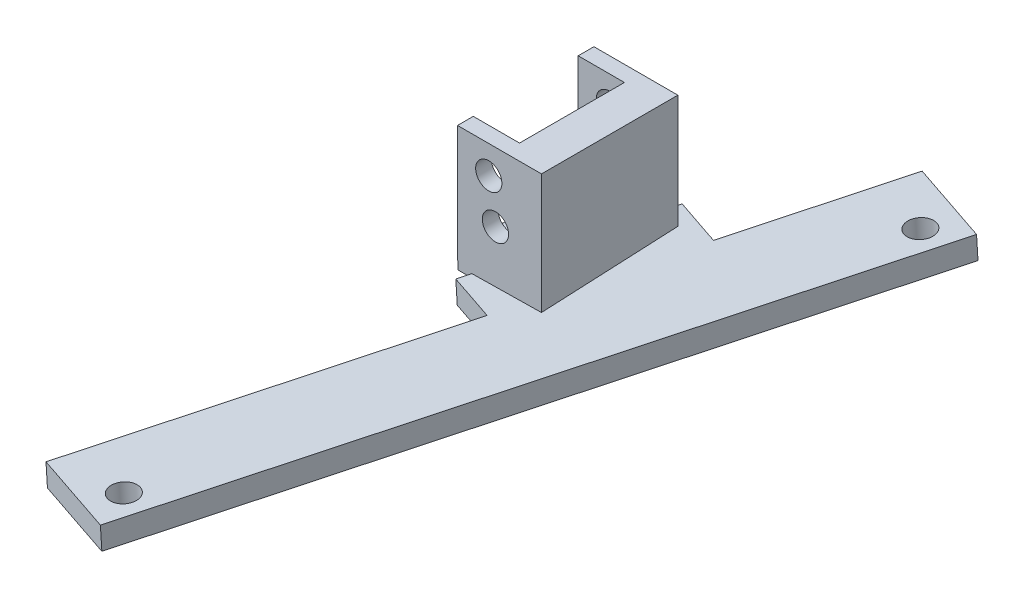
SolidWorks part; units mm, degrees
ref_plane "Front Plane" through (0, 0, 0) normal (0, 0, 1) x (1, 0, 0)
ref_plane "Top Plane" through (0, 0, 0) normal (0, 1, 0) x (1, 0, 0)
ref_plane "Right Plane" through (0, 0, 0) normal (1, 0, 0) x (0, 0, -1)
sketch "Sketch1" plane through (0, 0, 0) normal (0, 0, 1) x (1, 0, 0)
  line L0 (427.4923, 249.3739) -> (458.8626, 254.5214) construction
  line L1 (448.4353, 278.7761) -> (468.7553, 278.7761)
  line L2 (448.4353, 278.7761) -> (448.4353, 250.4861)
  line L3 (448.4353, 250.4861) -> (468.7553, 250.4861)
  line L4 (468.7553, 278.7761) -> (468.7553, 250.4861)
  line L5 (427.4923, 249.3739) -> (458.8626, 254.5214)
  line L6 (448.4353, 252.8104) -> (458.8626, 254.5214)
  arc A0 (461.3669, 277.5061) -> (454.7498, 279.5862) centre (455.9966, 271.9877) ccw construction
  arc A1 (463.4772, 270.1621) -> (461.3669, 277.5061) centre (455.9966, 271.9877) ccw construction
  arc A2 (463.4772, 270.1621) -> (464.1208, 266.2396) centre (468.4124, 268.9577) ccw construction
  arc A3 (464.4679, 258.6072) -> (464.1208, 266.2396) centre (457.6159, 262.1197) ccw construction
  arc A4 (458.8626, 254.5214) -> (464.4679, 258.6072) centre (457.6159, 262.1197) ccw construction
  arc A5 (461.3669, 277.5061) -> (454.7498, 279.5862) centre (455.9966, 271.9877) ccw
  arc A6 (463.4772, 270.1621) -> (461.3669, 277.5061) centre (455.9966, 271.9877) ccw
  arc A7 (463.4772, 270.1621) -> (464.1208, 266.2396) centre (468.4124, 268.9577) ccw
  arc A8 (464.4679, 258.6072) -> (464.1208, 266.2396) centre (457.6159, 262.1197) ccw
  arc A9 (458.8626, 254.5214) -> (464.4679, 258.6072) centre (457.6159, 262.1197) ccw
  arc A10 (458.8626, 254.5214) -> (464.4679, 258.6072) centre (457.6159, 262.1197) ccw
  arc A11 (464.4679, 258.6072) -> (464.1208, 266.2396) centre (457.6159, 262.1197) ccw
  arc A12 (464.1208, 266.2396) -> (463.4772, 270.1621) centre (468.4124, 268.9577) cw
  arc A13 (463.4772, 270.1621) -> (461.3669, 277.5061) centre (455.9966, 271.9877) ccw
  arc A14 (461.3669, 277.5061) -> (459.6312, 278.7761) centre (455.9966, 271.9877) ccw
  circle A15 centre (457.6159, 262.1197) radius 3.175
  circle A16 centre (455.9966, 271.9877) radius 3.175
  dimension "D1" = 4.0353
  dimension "D2" = 1.27
  dimension "D3" = 20.32
  dimension "D4" = 10.16
extrude "Boss-Extrude1" add sketch "Sketch1" against normal blind 29.21 contours A9 L5 L2 L3 L4 L1 A5 A6 A7 A8
sketch "Sketch2" plane through (0, 0, 0) normal (0, 0, 1) x (1, 0, 0)
  line L0 (448.4353, 252.8104) -> (448.4353, 278.7761)
  line L1 (448.4353, 278.7761) -> (468.7553, 278.7761)
  line L2 (468.7553, 278.7761) -> (468.7553, 250.4861)
  line L3 (468.7553, 250.4861) -> (448.4353, 250.4861)
  line L4 (448.4353, 250.4861) -> (448.4353, 252.8104)
  circle A0 centre (455.9966, 271.9877) radius 3.175
  circle A1 centre (457.6159, 262.1197) radius 3.175
  dimension "D1" = 6.35
  dimension "D2" = 6.35
extrude "Boss-Extrude2" add sketch "Sketch2" along normal blind 3.81
sketch "Sketch3" plane through (0, 0, -25.4) normal (0, 0, -1) x (-1, 0, 0)
  line L0 (-448.4353, 252.8104) -> (-458.8626, 254.5214) construction
  line L1 (-448.4353, 252.8104) -> (-458.8626, 254.5214)
  line L2 (-448.4353, 252.8104) -> (-448.4353, 278.7761)
  line L3 (-448.4353, 278.7761) -> (-459.6312, 278.7761)
  line L4 (-458.8626, 254.5214) -> (-448.4353, 252.8104)
  arc A0 (-464.1208, 266.2396) -> (-458.8626, 254.5214) centre (-457.6159, 262.1197) ccw construction
  arc A1 (-464.1208, 266.2396) -> (-463.4772, 270.1621) centre (-468.4124, 268.9577) ccw construction
  arc A2 (-459.6312, 278.7761) -> (-463.4772, 270.1621) centre (-455.9966, 271.9877) ccw construction
  arc A3 (-464.1208, 266.2396) -> (-458.8626, 254.5214) centre (-457.6159, 262.1197) ccw
  arc A4 (-464.1208, 266.2396) -> (-463.4772, 270.1621) centre (-468.4124, 268.9577) ccw
  arc A5 (-459.6312, 278.7761) -> (-463.4772, 270.1621) centre (-455.9966, 271.9877) ccw
  arc A6 (-459.6312, 278.7761) -> (-463.4772, 270.1621) centre (-455.9966, 271.9877) ccw
  arc A7 (-463.4772, 270.1621) -> (-464.1208, 266.2396) centre (-468.4124, 268.9577) cw
  arc A8 (-464.1208, 266.2396) -> (-458.8626, 254.5214) centre (-457.6159, 262.1197) ccw
  circle A9 centre (-457.6159, 262.1197) radius 3.175
  circle A10 centre (-455.9966, 271.9877) radius 3.175
  line M4 (-423.8853, 271.3557) -> (-461.3669, 277.5061)
  arc M5 (-461.3669, 277.5061) -> (-463.4772, 270.1621) centre (-455.9966, 271.9877) ccw
  arc M6 (-463.4772, 270.1621) -> (-464.1208, 266.2396) centre (-468.4124, 268.9577) cw
  arc M7 (-464.1208, 266.2396) -> (-464.4679, 258.6072) centre (-457.6159, 262.1197) ccw
  line M8 (-464.4679, 258.6072) -> (-424.8406, 252.1047)
  circle M9 centre (-457.6159, 262.1197) radius 3.175
  circle M10 centre (-455.9966, 271.9877) radius 3.175
  dimension "D1" = 6.35
  dimension "D2" = 6.35
extrude "Boss-Extrude3" add sketch "Sketch3" along normal up to surface (3.81 mm away) contours L2 M8 M4 M5 M6 M7 M9 M10 | A3 L1 L2 M8 | L3 A5 L2 M4 up to face at (460.587, 262.6797, -29.21)
ref_plane "Plane1" through (-3.842, 241.8411, 11.4068) normal (-0.0159, 0.9988, 0.0471) x (0.9999, 0.0158, 0.0007)
sketch "Sketch4" plane through (-3.842, 241.8411, 11.4068) normal (-0.0159, 0.9988, 0.0471) x (0.9999, 0.0158, 0.0007)
  line L0 (459.2158, -85.5005) -> (512.6671, 73.3898)
  line L1 (512.6671, 73.3898) -> (492.8082, 80.0704)
  line L2 (492.8082, 80.0704) -> (480.0779, 42.228)
  line L3 (480.0779, 42.228) -> (468.6402, 46.0757)
  line L4 (468.6402, 46.0757) -> (454.8306, 5.0251)
  line L5 (454.8306, 5.0251) -> (466.2683, 1.1774)
  line L6 (466.2683, 1.1774) -> (439.3569, -78.8198)
  line L7 (439.3569, -78.8198) -> (459.2158, -85.5005)
  circle A0 centre (455.6747, -76.2696) radius 3.175
  circle A1 centre (504.2669, 68.1761) radius 3.175
  dimension "D6" = 39.9263
  dimension "D8" = 6.35
  dimension "D10" = 6.35
  dimension "D2" = 7.62
  dimension "D3" = 7.62
  dimension "D4" = 167.64
  dimension "D5" = 20.9525
  dimension "D7" = 84.4025
  dimension "D9" = 17.0596
  dimension "D11" = 20.9525
  dimension "D12" = 33.02
extrude "Boss-Extrude4" add sketch "Sketch4" against normal blind 5.588
sketch "Sketch5" plane through (0, 0, 3.81) normal (0, 0, 1) x (1, 0, 0)
  line L0 (468.7553, 250.4861) -> (448.5605, 250.4861)
  line L1 (448.4353, 250.4861) -> (468.7553, 250.4861) construction
  line L2 (448.5605, 250.4861) -> (448.5605, 248.529)
  line L3 (448.5605, 248.529) -> (468.7553, 248.3932)
  line L4 (468.7553, 248.3932) -> (468.7553, 250.4861)
extrude "Boss-Extrude5" add sketch "Sketch5" against normal up to surface (33.02 mm away) up to face at (460.0754, 260.1605, -29.21)
